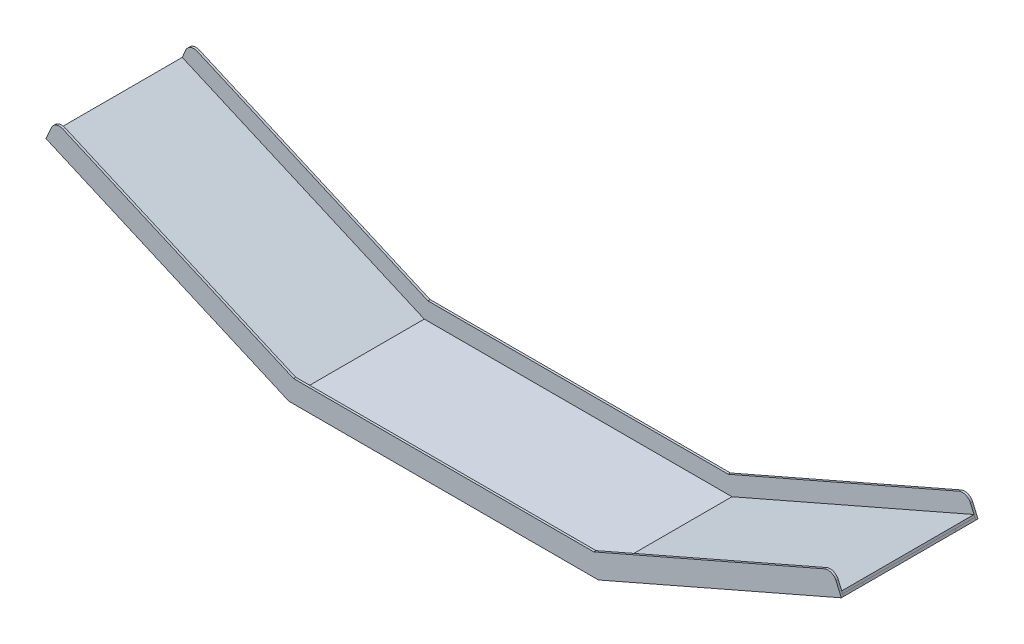
SolidWorks part; units mm, degrees
ref_plane "Plan de face" through (0, 0, 0) normal (0, 0, 1) x (1, 0, 0)
ref_plane "Plan de dessus" through (0, 0, 0) normal (0, 1, 0) x (1, 0, 0)
ref_plane "Plan de droite" through (0, 0, 0) normal (1, 0, 0) x (0, 0, -1)
sketch "Esquisse1" plane through (0, 0, 0) normal (0, 0, 1) x (1, 0, 0)
  line L0 (0, 0) -> (-275, -120)
  line L1 (-625, -120) -> (-275, -120)
  line L2 (-625, -120) -> (-900, 0)
  line L3 (-0.9999, 2.2913) -> (-275.5217, -117.5)
  line L4 (-624.4783, -117.5) -> (-275.5217, -117.5)
  line L5 (-624.4783, -117.5) -> (-899.0001, 2.2913)
  line L6 (-899.0001, 2.2913) -> (-900, 0)
  line L7 (-0.9999, 2.2913) -> (0, 0)
  dimension "D1" = 350
  dimension "D2" = 900
  dimension "D3" = 120
  dimension "D4" = 2.5
extrude "Boss.-Extru.1" add sketch "Esquisse1" along normal blind 150
sketch "Esquisse2" plane through (0, 0, 0) normal (0, 0, -1) x (-1, 0, 0)
  line L0 (0, 0) -> (275, -120)
  line L1 (275, -120) -> (625, -120)
  line L2 (625, -120) -> (900, 0)
  line L3 (900, 0) -> (900.9999, -2.2913)
  line L4 (900.9999, -2.2913) -> (625.5217, -122.5)
  line L5 (625.5217, -122.5) -> (274.4783, -122.5)
  line L6 (274.4783, -122.5) -> (-0.9999, -2.2913)
  line L7 (-0.9999, -2.2913) -> (0, 0)
  line L8 (625, -120) -> (624.4783, -117.5) construction
  line L9 (624.4783, -117.5) -> (628.626, -137.3761) construction
  line L10 (275.5217, -117.5) -> (275, -120) construction
  line L11 (275, -120) -> (268.2693, -152.2538) construction
  dimension "D1" = 2.5
  dimension "D2" = 2.5
  dimension "D3" = 2.5
extrude "Boss.-Extru.2" add sketch "Esquisse2" against normal blind 22.5 separate body
sketch "Esquisse3" plane through (0, 0, 150) normal (0, 0, 1) x (1, 0, 0)
  line L0 (-900, 0) -> (-900.9999, -2.2913)
  line L1 (-900.9999, -2.2913) -> (-625.5217, -122.5)
  line L2 (-625.5217, -122.5) -> (-900.9999, -2.2913) construction
  line L3 (-625.5217, -122.5) -> (-274.4783, -122.5)
  line L4 (-274.4783, -122.5) -> (0.9999, -2.2913)
  line L5 (0.9999, -2.2913) -> (0, 0)
  line L6 (0, 0) -> (-275, -120)
  line L7 (-275, -120) -> (-625, -120)
  line L8 (-625, -120) -> (-900, 0)
extrude "Boss.-Extru.3" add sketch "Esquisse3" against normal blind 22.5 separate body
sketch "Esquisse4" plane through (0, 0, 127.5) normal (0, 0, -1) x (-1, 0, 0)
  line L0 (900.9999, -2.2913) -> (900, 0)
  line L1 (900, 0) -> (877.0865, -9.9986)
  line L2 (625, -120) -> (900, 0) construction
  line L3 (877.0865, -9.9986) -> (878.0864, -12.29)
  line L4 (900.9999, -2.2913) -> (625.5217, -122.5) construction
  line L5 (878.0864, -12.29) -> (900.9999, -2.2913)
  line L6 (-0.9999, -2.2913) -> (0, 0)
  line L7 (0, 0) -> (22.9135, -9.9986)
  line L8 (0, 0) -> (275, -120) construction
  line L9 (22.9135, -9.9986) -> (21.9136, -12.29)
  line L10 (274.4783, -122.5) -> (-0.9999, -2.2913) construction
  line L11 (21.9136, -12.29) -> (-0.9999, -2.2913)
  dimension "D1" = 25
  dimension "D2" = 25
extrude "Boss.-Extru.4" add sketch "Esquisse4" along normal up to surface (105 mm away) separate body up to face at (-450, -61.1978, 22.5)
sketch "Esquisse5" plane through (0, 0, 150) normal (0, 0, 1) x (1, 0, 0)
  line L0 (0.9999, -2.2913) -> (-8.9988, 20.6221)
  line L1 (-8.9988, 20.6221) -> (-279.6953, -97.5)
  line L2 (-279.6953, -97.5) -> (-620.3047, -97.5)
  line L3 (-620.3047, -97.5) -> (-891.0012, 20.6221)
  line L4 (-891.0012, 20.6221) -> (-900.9999, -2.2913)
  line L5 (-900.9999, -2.2913) -> (-625.5217, -122.5)
  line L6 (-625.5217, -122.5) -> (-274.4783, -122.5)
  line L7 (-274.4783, -122.5) -> (0.9999, -2.2913)
  line L8 (-274.4783, -122.5) -> (-275.5217, -117.5) construction
  line L9 (-275.5217, -117.5) -> (-274.4848, -122.469) construction
  line L10 (-625.5217, -122.5) -> (-624.4783, -117.5) construction
  line L12 (-624.4783, -117.5) -> (-622.2449, -106.7977) construction
  line L13 (-274.4783, -122.5) -> (0.9999, -2.2913) construction
  line L14 (0.9999, -2.2913) -> (0, 0) construction
  dimension "D1" = 25
  dimension "D2" = 25
  dimension "D3" = 25
extrude "Boss.-Extru.5" add sketch "Esquisse5" along normal blind 2.5 separate body
sketch "Esquisse6" plane through (0, 0, 0) normal (0, 0, -1) x (-1, 0, 0)
  line L0 (8.9988, 20.6221) -> (-0.9999, -2.2913)
  line L1 (-0.9999, -2.2913) -> (274.4783, -122.5)
  line L2 (-0.9999, -2.2913) -> (274.4783, -122.5) construction
  line L3 (274.4783, -122.5) -> (625.5217, -122.5)
  line L4 (625.5217, -122.5) -> (900.9999, -2.2913)
  line L5 (900.9999, -2.2913) -> (891.0012, 20.6221)
  line L6 (891.0012, 20.6221) -> (620.3047, -97.5)
  line L7 (620.3047, -97.5) -> (279.6953, -97.5)
  line L8 (279.6953, -97.5) -> (8.9988, 20.6221)
extrude "Boss.-Extru.6" add sketch "Esquisse6" along normal blind 2.5 separate body
fillet "Congé1" radius 10 1 edges at (-891.0012, 20.6221, -1.25)
fillet "Congé2" radius 10 1 edges at (-891.0012, 20.6221, 151.25)
fillet "Congé3" radius 10 1 edges at (-8.9988, 20.6221, 151.25)
fillet "Congé4" radius 10 1 edges at (-8.9988, 20.6221, -1.25)
